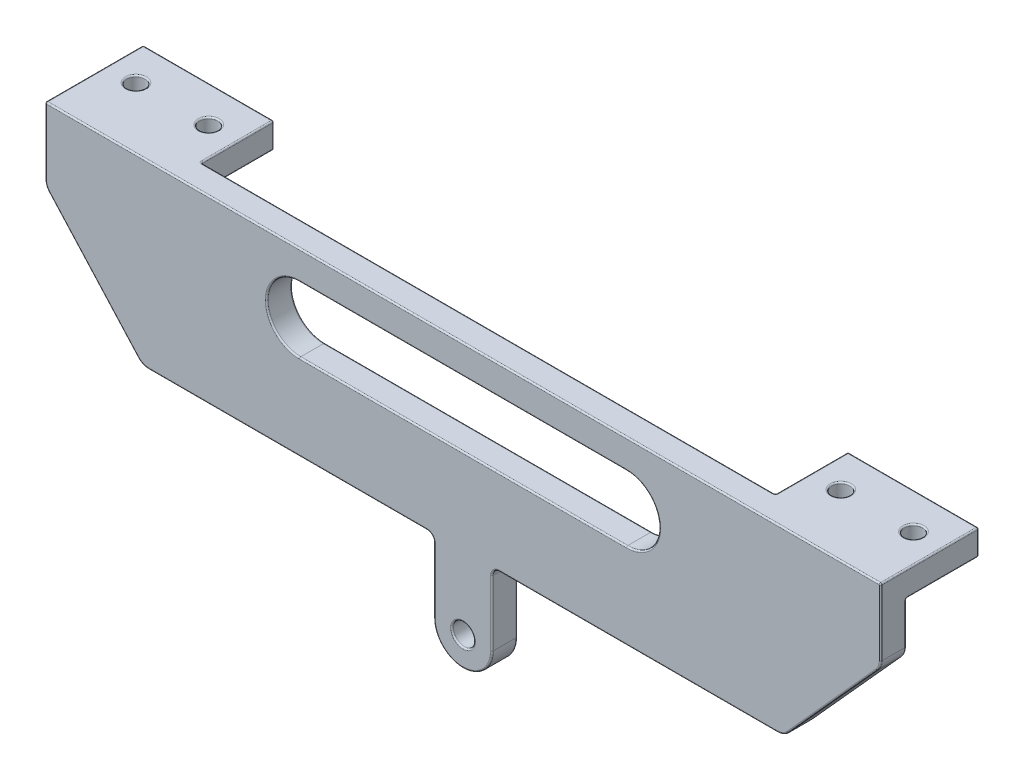
SolidWorks part; units mm, degrees
ref_plane "Front Plane" through (0, 0, 0) normal (0, 0, 1) x (1, 0, 0)
ref_plane "Top Plane" through (0, 0, 0) normal (0, 1, 0) x (1, 0, 0)
ref_plane "Right Plane" through (0, 0, 0) normal (1, 0, 0) x (0, 0, -1)
sketch "Sketch1" plane through (0, 0, 0) normal (0, 0, 1) x (1, 0, 0)
  line L0 (-100, 0) -> (100, 0) construction
  line L1 (-100, 0) -> (0, 100) construction
  line L2 (0, 100) -> (100, 0) construction
  line L3 (0, 0) -> (-50, 50) construction
  line L4 (-40, 60) -> (40, 60) construction
  line L5 (0, 100) -> (0, 60) construction
  circle A0 centre (-100, 0) radius 20
  circle A1 centre (0, 0) radius 20
  circle A2 centre (100, 0) radius 20
  point P2 (0, 0)
  dimension "D5" = 40
  dimension "D1" = 200
  dimension "D2" = 90
  dimension "D3" = 90
  dimension "D4" = 80
sketch "Sketch2" plane through (0, 0, 0) normal (0, 0, 1) x (1, 0, 0)
  line L0 (-56.5165, 43.4835) -> (-40, 60) construction
  line L1 (-100, 0) -> (0, 100) construction
  line L2 (-40, 60) -> (40, 60) construction
  line L3 (40, 60) -> (86.565, 13.435) construction
  line L4 (0, 100) -> (100, 0) construction
  line L5 (-49.4454, 36.4124) -> (-35.8579, 50)
  line L6 (-35.8579, 50) -> (35.8579, 50)
  line L7 (35.8579, 50) -> (79.4939, 6.364)
  line L8 (-63.5876, 50.5546) -> (-44.1421, 70)
  line L9 (-44.1421, 70) -> (44.1421, 70)
  line L10 (44.1421, 70) -> (93.636, 20.5061)
  line L11 (-63.5876, 50.5546) -> (-49.4454, 36.4124)
  line L12 (93.636, 20.5061) -> (79.4939, 6.364)
  line L13 (90.9809, 17.8509) -> (104.534, 4.6576)
  line L14 (82.1491, 9.0191) -> (95.3424, -4.534)
  line L15 (90.1005, 24.0416) -> (75.9584, 9.8995)
  line L16 (0, 100) -> (0, 60) construction
  line L17 (-6, 70) -> (-3.4532, 85.4203)
  line L18 (6, 70) -> (3.4532, 85.4203)
  circle A0 centre (100, 0) radius 3.5
  circle A1 centre (100, 0) radius 10 construction
  arc A2 (95.3424, -4.534) -> (104.534, 4.6576) centre (100, 0) ccw
  circle A3 centre (100, 0) radius 0.5
  circle A4 centre (100, 0) radius 20 construction
  circle A5 centre (100, 0) radius 6.5 construction
  circle A6 centre (79.4939, 13.435) radius 1
  circle A7 centre (86.565, 20.5061) radius 1
  circle A8 centre (0, 60) radius 1.5
  circle A9 centre (0, 84.85) radius 1.5
  arc A10 (3.4532, 85.4203) -> (-3.4532, 85.4203) centre (0, 84.85) ccw
  circle A11 centre (0, 84.85) radius 3.5 construction
  circle A12 centre (-50, 50) radius 1.5
  dimension "D4" = 20
  dimension "D5" = 7
  dimension "D10" = 2
  dimension "D13" = 3
  dimension "D18" = 3
  dimension "D3" = 27.5
  dimension "D8" = 19
  dimension "D9" = 5
  dimension "D11" = 5
  dimension "D12" = 5
  dimension "D14" = 14.85
  dimension "D16" = 6
  dimension "D17" = 6
  dimension "D1" = 10
  dimension "D2" = 10
  dimension "D6" = 3
  dimension "D7" = 3
  dimension "D15" = 2
sketch "Sketch3" plane through (0, 0, 0) normal (0, 0, 1) x (1, 0, 0)
  line L1 (-100, 0) -> (0, 100) construction
  line L2 (-86.565, 13.435) -> (-50, 50) construction
  line L3 (-50, 50) -> (-13.435, 13.435) construction
  line L4 (0, 0) -> (-50, 50) construction
  line L5 (-93.636, 20.5061) -> (-50, 64.1421)
  line L6 (-50, 64.1421) -> (-6.364, 20.5061)
  line L7 (-79.4939, 6.364) -> (-50, 35.8579)
  line L8 (-50, 35.8579) -> (-20.5061, 6.364)
  line L9 (-93.636, 20.5061) -> (-50, 64.1421) construction
  line L10 (-79.4939, 6.364) -> (-50, 35.8579) construction
  line L11 (-93.636, 20.5061) -> (-79.4939, 6.364)
  line L12 (-6.364, 20.5061) -> (-20.5061, 6.364)
  line L13 (-104.5962, 4.5962) -> (-91.2218, 17.9706)
  line L14 (-95.4038, -4.5962) -> (-82.0294, 8.7782)
  line L15 (-17.9706, 8.7782) -> (-4.5962, -4.5962)
  line L16 (-8.7782, 17.9706) -> (4.5962, 4.5962)
  line L17 (-90.1005, 24.0416) -> (-75.9584, 9.8995) construction
  line L18 (-24.0416, 9.8995) -> (-9.8995, 24.0416) construction
  circle A0 centre (-100, 0) radius 10 construction
  circle A1 centre (-100, 0) radius 3.5
  circle A2 centre (0, 0) radius 3.5
  circle A3 centre (0, 0) radius 10 construction
  arc A4 (-4.5962, -4.5962) -> (4.5962, 4.5962) centre (0, 0) ccw
  arc A5 (-104.5962, 4.5962) -> (-95.4038, -4.5962) centre (-100, 0) ccw
  circle A6 centre (-86.565, 20.5061) radius 1
  circle A7 centre (-100, 0) radius 20 construction
  circle A8 centre (0, 0) radius 20 construction
  circle A9 centre (-100, 0) radius 6.5 construction
  circle A10 centre (0, 0) radius 6.5 construction
  circle A11 centre (-79.4939, 13.435) radius 1
  circle A12 centre (-20.5061, 13.435) radius 1
  circle A13 centre (-13.435, 20.5061) radius 1
  circle A14 centre (-50, 50) radius 1.5 construction
  circle A15 centre (-50, 50) radius 1.5
  dimension "D1" = 20
  dimension "D2" = 7
  dimension "D8" = 2
  dimension "D6" = 19
  dimension "D7" = 19
  dimension "D9" = 5
  dimension "D10" = 5
  dimension "D11" = 5
  dimension "D12" = 5
  dimension "D13" = 5
  dimension "D14" = 5
  dimension "D3" = 3
  dimension "D4" = 10
  dimension "D5" = 10
sketch "Sketch4" plane through (0, 0, 0) normal (0, 0, 1) x (1, 0, 0)
  line L0 (-57.5, 94.8011) -> (57.5, 94.8011)
  line L1 (57.5, 94.8011) -> (57.5, 84.8011)
  line L2 (57.5, 84.8011) -> (44.1421, 70)
  line L3 (44.1421, 70) -> (-44.1421, 70)
  line L4 (-44.1421, 70) -> (-57.5, 84.8011)
  line L5 (-57.5, 84.8011) -> (-57.5, 94.8011)
  line L6 (4, 60) -> (4, 70)
  line L7 (-4, 60) -> (-4, 70)
  line L9 (-22.5, 86.3011) -> (22.5, 86.3011) construction
  line L10 (-22.5, 90.8011) -> (22.5, 90.8011)
  line L11 (-22.5, 81.8011) -> (22.5, 81.8011)
  circle A0 centre (0, 60) radius 1.5 construction
  circle A1 centre (0, 60) radius 1.5
  arc A2 (-4, 60) -> (4, 60) centre (0, 60) ccw
  circle A3 centre (0, 60) radius 4 construction
  arc A4 (-22.5, 90.8011) -> (-22.5, 81.8011) centre (-22.5, 86.3011) ccw
  arc A5 (22.5, 81.8011) -> (22.5, 90.8011) centre (22.5, 86.3011) ccw
  point P19 (0, 86.3011)
  dimension "D1" = 115
  dimension "D2" = 10
  dimension "D3" = 2.5
  dimension "D4" = 45
  dimension "D5" = 9
  dimension "D6" = 4
sketch "Sketch5" plane through (0, 0, 0) normal (0, 0, 1) x (1, 0, 0)
  line L0 (4, 60) -> (4, 70) construction
  line L1 (-4, 60) -> (-4, 70) construction
  line L2 (22.5, 90.8011) -> (-22.5, 90.8011)
  line L3 (-22.5, 81.8011) -> (22.5, 81.8011)
  line L4 (22.5, 90.8011) -> (-22.5, 90.8011)
  line L5 (-22.5, 81.8011) -> (22.5, 81.8011)
  line L6 (57.5, 94.8011) -> (-57.5, 94.8011)
  line L7 (57.5, 84.8011) -> (57.5, 94.8011)
  line L8 (44.1421, 70) -> (57.5, 84.8011)
  line L9 (-44.1421, 70) -> (44.1421, 70)
  line L10 (-57.5, 84.8011) -> (-44.1421, 70)
  line L11 (-57.5, 94.8011) -> (-57.5, 84.8011)
  line L12 (57.5, 94.8011) -> (-57.5, 94.8011)
  line L13 (57.5, 84.8011) -> (57.5, 94.8011)
  line L14 (44.1421, 70) -> (57.5, 84.8011)
  line L15 (-44.1421, 70) -> (-4, 70)
  line L16 (-57.5, 84.8011) -> (-44.1421, 70)
  line L17 (-57.5, 94.8011) -> (-57.5, 84.8011)
  line L18 (4, 60) -> (4, 70)
  line L19 (-4, 60) -> (-4, 70)
  line L20 (4, 70) -> (44.1421, 70)
  arc A0 (-4, 60) -> (4, 60) centre (0, 60) ccw construction
  circle A1 centre (0, 60) radius 1.5
  circle A2 centre (0, 60) radius 1.5
  arc A3 (-4, 60) -> (4, 60) centre (0, 60) ccw
  arc A4 (22.5, 81.8011) -> (22.5, 90.8011) centre (22.5, 86.3011) ccw
  arc A5 (-22.5, 90.8011) -> (-22.5, 81.8011) centre (-22.5, 86.3011) ccw
  arc A6 (22.5, 81.8011) -> (22.5, 90.8011) centre (22.5, 86.3011) ccw
  arc A7 (-22.5, 90.8011) -> (-22.5, 81.8011) centre (-22.5, 86.3011) ccw
  dimension "D1" = 0
  dimension "D2" = 0
  dimension "D3" = 0
extrude "Boss-Extrude1" add sketch "Sketch5" along normal blind 3.5
sketch "Sketch6" plane through (0, 94.8011, 0) normal (0, 1, 0) x (1, 0, 0)
  line L0 (-57.5, 0) -> (-39.5, 0)
  line L1 (57.5, 0) -> (-57.5, 0) construction
  line L2 (-39.5, 0) -> (-39.5, 10)
  line L3 (-39.5, 10) -> (-57.5, 10)
  line L4 (-57.5, 10) -> (-57.5, 0)
  line L5 (-57.5, 5) -> (-39.5, 5) construction
  line L6 (-48.5, 5) -> (-48.5, 10) construction
  line L7 (0, 0) -> (0, 26.3824) construction
  line L8 (48.5, 5) -> (48.5, 10) construction
  line L9 (57.5, 5) -> (39.5, 5) construction
  line L10 (57.5, 10) -> (57.5, 0)
  line L11 (39.5, 10) -> (57.5, 10)
  line L12 (39.5, 0) -> (39.5, 10)
  line L13 (57.5, 0) -> (39.5, 0)
  circle A0 centre (-53.5, 5) radius 1.25
  circle A1 centre (-43.5, 5) radius 1.25
  circle A2 centre (43.5, 5) radius 1.25
  circle A3 centre (53.5, 5) radius 1.25
  dimension "D4" = 2.5
  dimension "D1" = 18
  dimension "D2" = 10
  dimension "D3" = 10
extrude "Boss-Extrude2" add sketch "Sketch6" against normal blind 3.5
fillet "Fillet1" radius 2 4 edges at (57.5, 84.8011, 1.75) (44.1421, 70, 1.75) (-44.1421, 70, 1.75) (-57.5, 84.8011, 1.75)
fillet "Fillet2" radius 1 2 edges at (4, 70, 1.75) (-4, 70, 1.75)
fillet "Fillet4" radius 0.2 70 edges at (53.5, 94.8011, -6.25) (53.5, 91.3011, -6.25) (43.5, 94.8011, -6.25) (43.5, 91.3011, -6.25) (48.5, 94.8011, -10) (48.5, 91.3011, -10) (39.5, 94.8011, -5) (39.5, 91.3011, -5) (48.5, 91.3011, 0) (57.5, 91.3011, -5) (39.5, 93.0511, -10) (39.5, 93.0511, 0) (57.5, 93.0511, -10) (-43.5, 94.8011, -3.75) (-43.5, 91.3011, -3.75) (-53.5, 94.8011, -3.75) (-53.5, 91.3011, -3.75) (-39.5, 94.8011, -5) (-39.5, 91.3011, -5) (-48.5, 94.8011, -10) (-48.5, 91.3011, -10) (-57.5, 91.3011, -5) (-48.5, 91.3011, 0) (-39.5, 93.0511, 0) (-39.5, 93.0511, -10) (-57.5, 93.0511, -10) (0, 81.8011, 0) (27, 86.3011, 0) (0, 90.8011, 0) (-27, 86.3011, 3.5) (0, 81.8011, 3.5) (27, 86.3011, 3.5) (0, 90.8011, 3.5) (1.5, 60, 0) (1.5, 60, 3.5) (-57.5, 88.4356, 0) (-50.8613, 77.4451, 0) (-24.1265, 70, 0) (-4, 64.5, 0) (0, 56, 0) (4, 64.5, 0) (24.1265, 70, 0) (50.8613, 77.4451, 0) (57.5, 88.4356, 0) (0, 94.8011, 0) (-57.5, 90.1856, 3.5) (-50.8613, 77.4451, 3.5) (-24.1265, 70, 3.5) (-4, 64.5, 3.5) (0, 56, 3.5) (4, 64.5, 3.5) (24.1265, 70, 3.5) (50.8613, 77.4451, 3.5) (57.5, 90.1856, 3.5) (0, 94.8011, 3.5) (-57.5, 94.8011, -3.25) (57.5, 94.8011, -3.25) (-57.3667, 84.8523, 0) (-44.0655, 70.1724, 0) (44.0655, 70.1724, 0) (57.3667, 84.8523, 0) (-57.3667, 84.8523, 3.5) (-44.0655, 70.1724, 3.5) (44.0655, 70.1724, 3.5) (57.3667, 84.8523, 3.5) (4.2929, 69.7071, 0) (4.2929, 69.7071, 3.5) (-4.2929, 69.7071, 0) (-4.2929, 69.7071, 3.5) (-27, 86.3011, 0)
